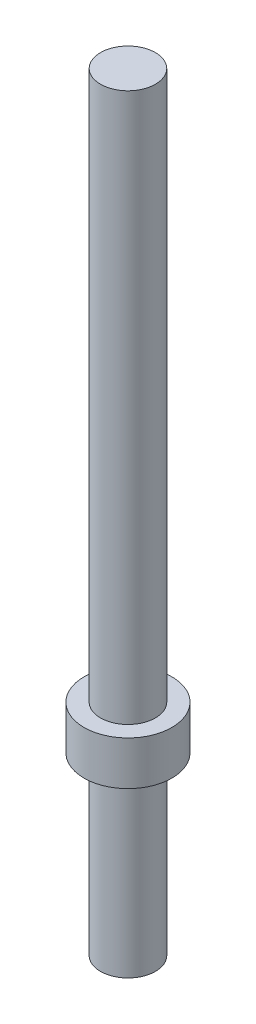
SolidWorks part; units mm, degrees
ref_plane "Front Plane" through (0, 0, 0) normal (0, 0, 1) x (1, 0, 0)
ref_plane "Top Plane" through (0, 0, 0) normal (0, 1, 0) x (1, 0, 0)
ref_plane "Right Plane" through (0, 0, 0) normal (1, 0, 0) x (0, 0, -1)
sketch "Sketch1" plane through (0, 0, 0) normal (0, 1, 0) x (1, 0, 0)
  circle A0 centre (0, 0) radius 2.5
extrude "Boss-Extrude1" add sketch "Sketch1" along normal blind 50
sketch "Sketch2" plane through (0, 0, 0) normal (0, 1, 0) x (1, 0, 0)
  circle A0 centre (0, 0) radius 4
extrude "Boss-Extrude2" add sketch "Sketch2" against normal blind 4
sketch "Sketch3" plane through (0, 0, 0) normal (0, 1, 0) x (1, 0, 0)
  circle A0 centre (0, 0) radius 2.5
extrude "Boss-Extrude3" add sketch "Sketch3" against normal blind 20
